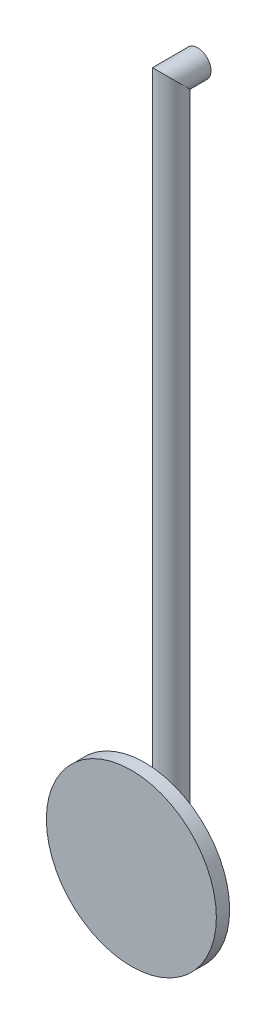
SolidWorks part; units mm, degrees
ref_plane "前视基准面" through (0, 0, 0) normal (0, 0, 1) x (1, 0, 0)
ref_plane "上视基准面" through (0, 0, 0) normal (0, 1, 0) x (1, 0, 0)
ref_plane "右视基准面" through (0, 0, 0) normal (1, 0, 0) x (0, 0, -1)
sketch "草图1" plane through (0, 0, 0) normal (0, 0, 1) x (1, 0, 0)
  line L0 (-44.2368, 0) -> (41.6485, 0) construction
  line L1 (0, 42.3019) -> (0, -39.6233) construction
  circle A0 centre (0, 0) radius 32
  point P7 (0, 32)
  dimension "D1" = 64
sketch "草图2" plane through (0, 0, 0) normal (1, 0, 0) x (0, 0, -1)
  line L0 (0, 0) -> (15, 0)
  line L1 (15, 0) -> (15, 250)
  line L2 (15, 250) -> (25, 250)
  dimension "D1" = 15
  dimension "D2" = 250
  dimension "D3" = 10
ref_plane "基准面4" through (0, 0, -25) normal (0, 0, 1) x (1, 0, 0)
ref_plane "基准面5" through (0, 0, -15) normal (0, 0, 1) x (1, 0, 0)
extrude "凸台-拉伸2" add sketch "草图1" against normal blind 5 contours A0
sketch "草图5" plane through (0, 0, -5) normal (0, 0, 1) x (1, 0, 0)
  line L0 (0, 32) -> (0, -38.1489) construction
  line L1 (0, 42.3019) -> (0, -39.6233) construction
  line L2 (-40.4401, 0) -> (36.9394, 0) construction
  line L3 (-44.2368, 0) -> (41.6485, 0) construction
  circle A0 centre (0, 0) radius 5
  circle A1 centre (0, 0) radius 32 construction
  point P13 (0, 5)
  dimension "D1" = 10
sweep "扫描1" add profiles "草图5" path "草图2"
